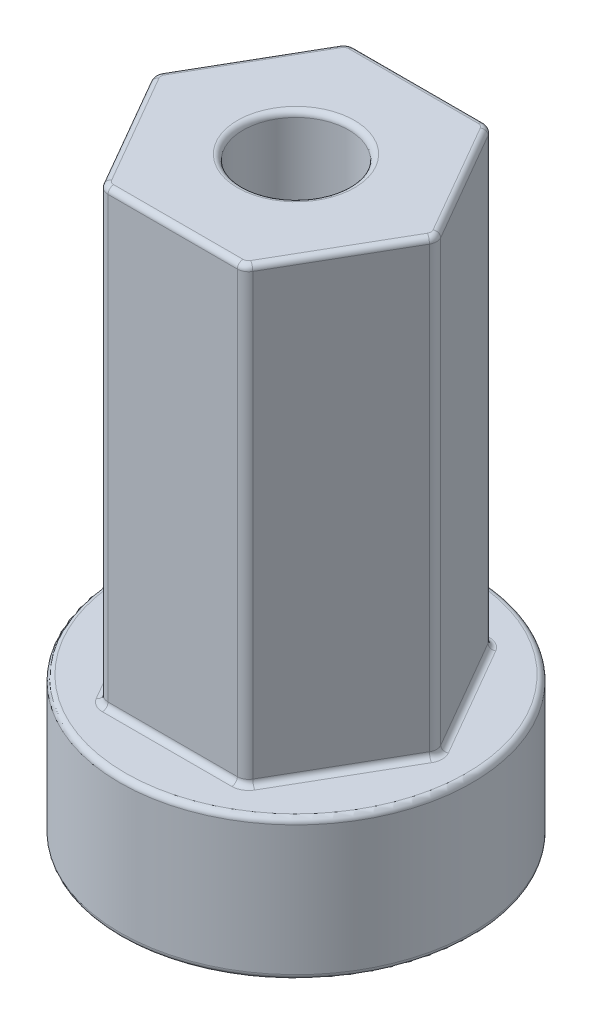
SolidWorks part; units mm, degrees
material "AISI 304"
ref_plane "Front" through (0, 0, 0) normal (0, 0, 1) x (1, 0, 0)
ref_plane "Top" through (0, 0, 0) normal (0, 1, 0) x (1, 0, 0)
ref_plane "Right" through (0, 0, 0) normal (1, 0, 0) x (0, 0, -1)
sketch "Sketch1" plane through (0, 0, 0) normal (0, 1, 0) x (1, 0, 0)
  circle A0 centre (0, 0) radius 7.9375
  dimension "D1" = 15.875
extrude "Extrude1" add sketch "Sketch1" along normal blind 6.35
sketch "Sketch2" plane through (0, 6.35, 0) normal (0, 1, 0) x (-1, 0, 0)
  line L1 (6.4158, 0) -> (3.2079, 5.5563)
  line L2 (3.2079, 5.5563) -> (-3.2079, 5.5563)
  line L3 (-3.2079, 5.5563) -> (-6.4158, 0)
  line L4 (-6.4158, 0) -> (-3.2079, -5.5562)
  line L5 (-3.2079, -5.5562) -> (3.2079, -5.5562)
  line L6 (3.2079, -5.5562) -> (6.4158, 0)
  circle A0 centre (0, 0) radius 5.5562 construction
  dimension "D1" = 11.1125
extrude "Extrude2" add sketch "Sketch2" along normal blind 20.32
sketch "Sketch3" plane through (0, 26.67, 0) normal (0, 1, 0) x (-1, 0, 0)
  circle A0 centre (0, 0) radius 2.3813
  dimension "D1" = 4.7625
extrude "Cut-Extrude1" cut sketch "Sketch3" against normal through all
fillet "Fillet1" radius 0.508 6 edges at (-3.2079, 16.51, -5.5562) (3.2079, 16.51, -5.5562) (6.4158, 16.51, 0) (3.2079, 16.51, 5.5563) (-3.2079, 16.51, 5.5563) (-6.4158, 16.51, 0)
fillet "Fillet2" radius 0.254 28 edges at (0, 0, 7.9375) (0, 0, 2.3813) (3.1686, 26.67, -5.4882) (4.8119, 26.67, -2.7781) (6.3372, 26.67, 0) (4.8119, 26.67, 2.7781) (3.1686, 26.67, 5.4882) (0, 26.67, 5.5563) (-3.1686, 26.67, 5.4882) (-4.8119, 26.67, 2.7781) (-6.3372, 26.67, 0) (-4.8119, 26.67, -2.7781) (-3.1686, 26.67, -5.4882) (0, 26.67, -5.5562) (0, 26.67, 2.3813) (-3.1686, 6.35, 5.4882) (0, 6.35, 5.5563) (3.1686, 6.35, 5.4882) (4.8119, 6.35, 2.7781) (6.3372, 6.35, 0) (4.8119, 6.35, -2.7781) (3.1686, 6.35, -5.4882) (0, 6.35, -5.5562) (-3.1686, 6.35, -5.4882) (-4.8119, 6.35, -2.7781) (-6.3372, 6.35, 0) (-4.8119, 6.35, 2.7781) (0, 6.35, 7.9375)
